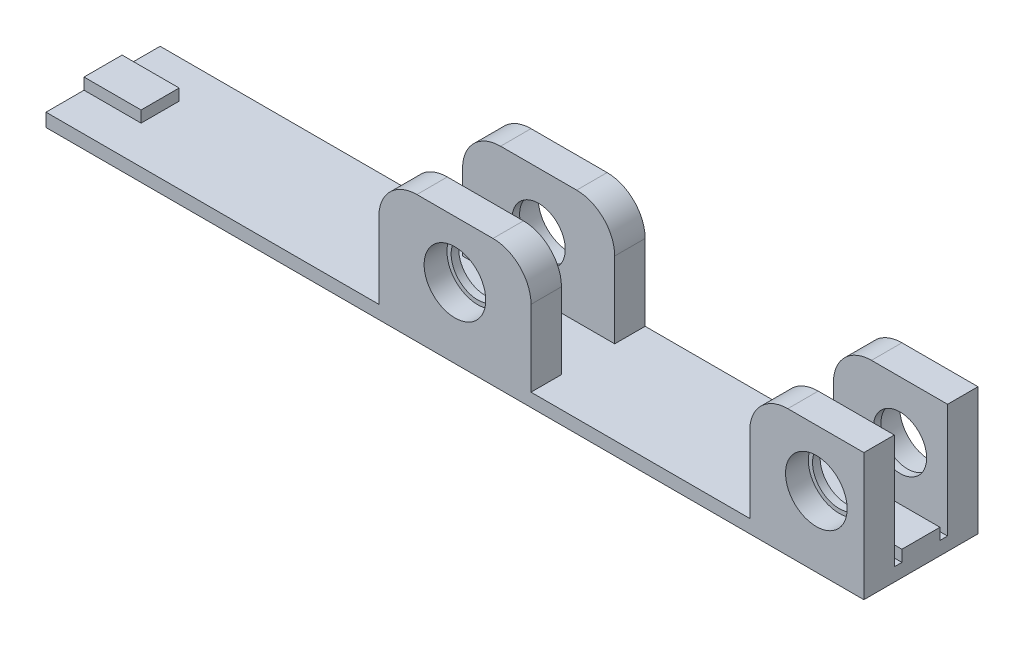
SolidWorks part; units mm, degrees
ref_plane "Front Plane" through (0, 0, 0) normal (0, 0, 1) x (1, 0, 0)
ref_plane "Top Plane" through (0, 0, 0) normal (0, 1, 0) x (1, 0, 0)
ref_plane "Right Plane" through (0, 0, 0) normal (1, 0, 0) x (0, 0, -1)
sketch "Sketch2" plane through (0, 0, 0) normal (0, 1, 0) x (1, 0, 0)
  line L1 (107.5, 15) -> (-107.5, 15)
  line L2 (107.5, 15) -> (107.5, -15)
  line L3 (107.5, -15) -> (-107.5, -15)
  line L4 (-107.5, 15) -> (-107.5, -15)
  line L5 (107.5, 15) -> (-107.5, -15) construction
  line L6 (107.5, -15) -> (-107.5, 15) construction
  point P0 (0, 0)
  dimension "D1" = 215
  dimension "D2" = 30
extrude "Boss-Extrude1" add sketch "Sketch2" along normal blind 3.5
sketch "HOLES TBD" plane through (0, 3.5, 0) normal (0, 1, 0) x (1, 0, 0)
  line L0 (100, 0) -> (-100, 0) construction
  circle A0 centre (-100, 0) radius 1.65
  circle A1 centre (100, 0) radius 1.65
  point P4 (0, 0)
  dimension "D2" = 3.3
  dimension "D1" = 200
sketch "Sketch4" plane through (0, 3.5, 0) normal (0, 1, 0) x (1, 0, 0)
  line L0 (-107.5, -15) -> (107.5, -15) construction
  line L1 (107.5, -15) -> (77.5, -15)
  line L2 (107.5, -15) -> (107.5, -7)
  line L3 (107.5, -7) -> (77.5, -7)
  line L4 (77.5, -15) -> (77.5, -7)
  line L5 (107.5, -15) -> (77.5, -7) construction
  line L6 (107.5, -7) -> (77.5, -15) construction
  line L7 (-20, -15) -> (20, -15)
  line L8 (-20, -15) -> (-20, -7)
  line L9 (-20, -7) -> (20, -7)
  line L10 (20, -15) -> (20, -7)
  line L11 (-20, -15) -> (20, -7) construction
  line L12 (-20, -7) -> (20, -15) construction
  line L13 (0, 0) -> (0, -15) construction
  line L14 (-100, 0) -> (100, 0) construction
  line L15 (-20, 7) -> (20, 15) construction
  line L16 (-20, 15) -> (20, 7) construction
  line L17 (107.5, 7) -> (77.5, 15) construction
  line L18 (107.5, 15) -> (77.5, 7) construction
  line L19 (20, 15) -> (20, 7)
  line L20 (-20, 7) -> (20, 7)
  line L21 (-20, 15) -> (-20, 7)
  line L22 (-20, 15) -> (20, 15)
  line L23 (77.5, 15) -> (77.5, 7)
  line L24 (107.5, 7) -> (77.5, 7)
  line L25 (107.5, 15) -> (107.5, 7)
  line L26 (107.5, 15) -> (77.5, 15)
  point P4 (92.5, -11)
  point P10 (0, -11)
  point P28 (0, 11)
  point P29 (92.5, 11)
  dimension "D1" = 8
  dimension "D2" = 30
  dimension "D3" = 40
extrude "Boss-Extrude2" add sketch "Sketch4" along normal blind 30
sketch "Sketch5" plane through (0, 0, 15) normal (0, 0, 1) x (1, 0, 0)
  line L0 (0, 3.5) -> (0, 18.5) construction
  line L3 (0, 18.5) -> (95, 18.5) construction
  line L6 (20, 33.5) -> (20, 3.5) construction
  circle A0 centre (0, 18.5) radius 8.1
  circle A1 centre (95, 18.5) radius 8.1
  point P10 (20, 18.5)
  dimension "D2" = 16.2
  dimension "D3" = 95
extrude "Bearing holes" cut sketch "Sketch5" against normal blind 6
mirror "Mirror1" about plane through (0, 0, 0) normal (0, 0, 1) of "Bearing holes"
sketch "Sketch7" plane through (0, 0, 9) normal (0, 0, 1) x (1, 0, 0)
  circle A0 centre (0, 18.5) radius 7
  circle A1 centre (95, 18.5) radius 7
  dimension "D1" = 14
extrude "Cut-Extrude2" cut sketch "Sketch7" against normal through all
chamfer "Chamfer1" [suppressed] distance 5 angle 45
fillet "Fillet1" radius 10 6 edges at (-20, 33.5, 11) (-20, 33.5, -11) (20, 33.5, -11) (20, 33.5, 11) (77.5, 33.5, 11) (77.5, 33.5, -11)
extrude "Cut-Extrude1" cut sketch "HOLES TBD" against normal through all
sketch "Sketch6" plane through (0, 3.5, 0) normal (0, 1, 0) x (1, 0, 0)
  line L5 (-107.5, 0) -> (107.5, 0) construction
  line L6 (107.5, -7) -> (107.5, 7) construction
  line L7 (-107.5, 15) -> (-107.5, -15) construction
  line L8 (0, 0) -> (0, 7.2837) construction
  line L9 (-107.5, 5) -> (-92.5, 5)
  line L10 (-107.5, 5) -> (-107.5, -5)
  line L11 (-107.5, -5) -> (-92.5, -5)
  line L12 (-92.5, 5) -> (-92.5, -5)
  line L13 (107.5, -5) -> (92.5, -5)
  line L14 (92.5, 5) -> (92.5, -5)
  line L15 (107.5, 5) -> (92.5, 5)
  line L16 (107.5, 5) -> (107.5, -5)
  point P3 (-107.5, 0)
  point P11 (-92.5, 0)
  point P15 (0, 0)
  dimension "D1" = 10
  dimension "D2" = 15
extrude "Boss-Extrude3" add sketch "Sketch6" along normal blind 3
